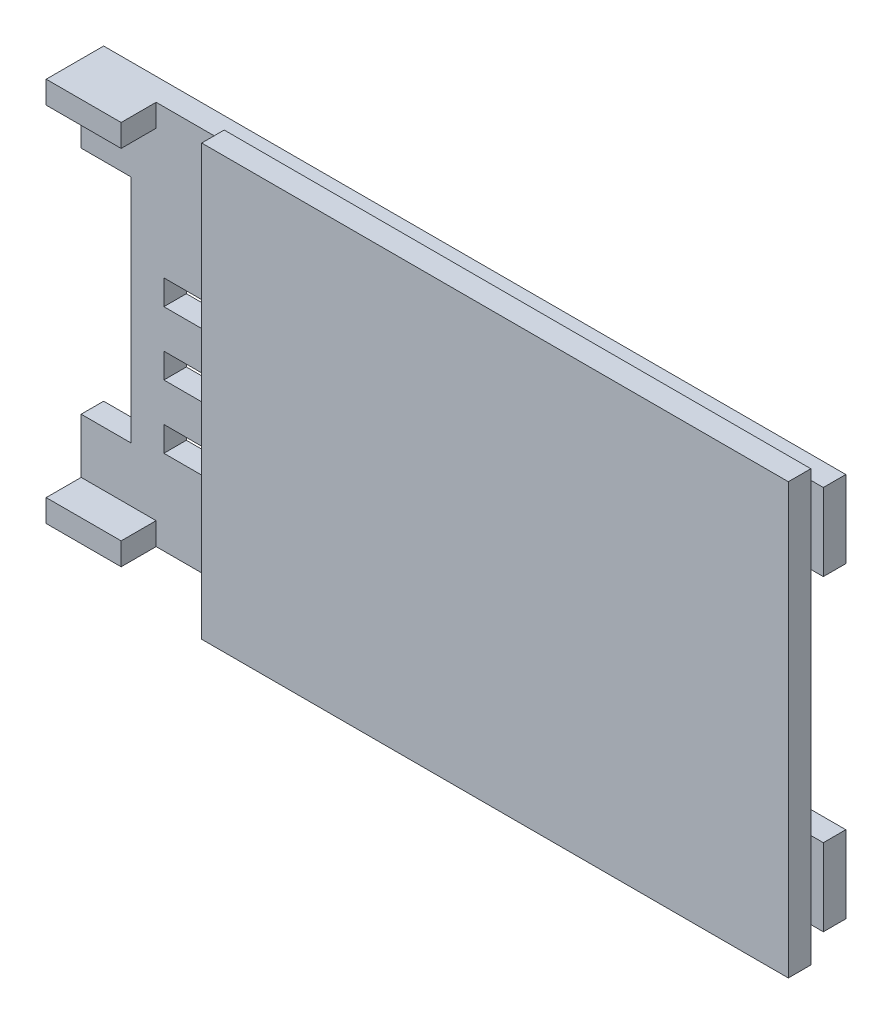
SolidWorks part; units mm, degrees
ref_plane "Front Plane" through (0, 0, 0) normal (0, 0, 1) x (1, 0, 0)
ref_plane "Top Plane" through (0, 0, 0) normal (0, 1, 0) x (1, 0, 0)
ref_plane "Right Plane" through (0, 0, 0) normal (1, 0, 0) x (0, 0, -1)
sketch "Sketch1" plane through (0, 0, 0) normal (0, 0, 1) x (1, 0, 0)
  line L0 (29.7, 12.31) -> (29.7, 15.4)
  line L1 (0, 0) -> (29.7, 0)
  line L2 (0, 0) -> (0, 3.09)
  line L3 (0, 15.4) -> (29.7, 15.4)
  line L4 (29.7, 0) -> (29.7, 3.09)
  line L5 (0, 12.31) -> (2, 12.31)
  line L6 (14.85, 15.4) -> (14.85, 0) construction
  line L7 (0, 3.09) -> (2, 3.09)
  line L8 (2, 12.31) -> (2, 3.09)
  line L9 (29.7, 12.31) -> (25.7, 12.31)
  line L10 (0, 12.31) -> (0, 15.4)
  line L11 (29.7, 3.09) -> (25.7, 3.09)
  line L12 (25.7, 12.31) -> (25.7, 3.09)
  line L13 (-2.6552, 7.7) -> (34.3923, 7.7) construction
  line L14 (-1.5692, 3.89) -> (31.5309, 3.89) construction
  line L15 (3.3098, 4.39) -> (9.6859, 4.39)
  line L16 (3.3098, 4.39) -> (3.3098, 3.39)
  line L17 (3.3098, 3.39) -> (9.6859, 3.39)
  line L18 (9.6859, 4.39) -> (9.6859, 3.39)
  line L19 (16.6164, 4.39) -> (22.3271, 4.39)
  line L20 (16.6164, 4.39) -> (16.6164, 3.39)
  line L21 (16.6164, 3.39) -> (22.3271, 3.39)
  line L22 (22.3271, 4.39) -> (22.3271, 3.39)
  line L23 (3.3098, 6.93) -> (9.6859, 6.93)
  line L24 (3.3098, 6.93) -> (3.3098, 5.93)
  line L25 (3.3098, 5.93) -> (9.6859, 5.93)
  line L26 (9.6859, 6.93) -> (9.6859, 5.93)
  line L27 (16.6164, 6.93) -> (22.3271, 6.93)
  line L28 (16.6164, 6.93) -> (16.6164, 5.93)
  line L29 (16.6164, 5.93) -> (22.3271, 5.93)
  line L30 (22.3271, 6.93) -> (22.3271, 5.93)
  line L31 (3.3098, 9.47) -> (9.6859, 9.47)
  line L32 (3.3098, 9.47) -> (3.3098, 8.47)
  line L33 (3.3098, 8.47) -> (9.6859, 8.47)
  line L34 (9.6859, 9.47) -> (9.6859, 8.47)
  line L35 (16.6164, 9.47) -> (22.3271, 9.47)
  line L36 (16.6164, 9.47) -> (16.6164, 8.47)
  line L37 (16.6164, 8.47) -> (22.3271, 8.47)
  line L38 (22.3271, 9.47) -> (22.3271, 8.47)
  point P17 (14.85, 7.7)
  point P18 (2, 7.7)
  point P19 (25.7, 7.7)
  point P30 (9.6859, 3.89)
  point P31 (22.3271, 3.89)
  dimension "D1" = 29.7
  dimension "D2" = 15.4
  dimension "D3" = 9.22
  dimension "D4" = 9.22
  dimension "D5" = 2
  dimension "D6" = 4
  dimension "D7" = 1
  dimension "D8" = 1
  dimension "D9" = 0.8
  dimension "D10" = 3
extrude "Boss-Extrude1" add sketch "Sketch1" along normal blind 0.9
ref_plane "Plane1" through (0, 0, 2.3) normal (0, 0, -1) x (-1, 0, 0)
sketch "Sketch4" plane through (0, 0, 0.9) normal (0, 0, 1) x (1, 0, 0)
  line L0 (25.7, 12.31) -> (25.7, 3.09) construction
  line L1 (0, 15.4) -> (3, 15.4)
  line L2 (0, 15.4) -> (0, 14.5)
  line L3 (0, 14.5) -> (3, 14.5)
  line L4 (3, 15.4) -> (3, 14.5)
  line L5 (25.7, 7.7) -> (2, 7.7) construction
  line L6 (2, 12.31) -> (2, 3.09) construction
  line L7 (3, 0) -> (3, 0.9)
  line L8 (0, 0.9) -> (3, 0.9)
  line L9 (0, 0) -> (0, 0.9)
  line L10 (0, 0) -> (3, 0)
  dimension "D1" = 3
  dimension "D2" = 0.9
extrude "Boss-Extrude3" add sketch "Sketch4" along normal up to surface (1.4 mm away) up to plane "Plane1"
sketch "Sketch5" plane through (0, 0, 2.3) normal (0, 0, -1) x (-1, 0, 0)
  line L0 (-25.7, 12.31) -> (-25.7, 3.09) construction
  line L1 (-6.2237, -0.9) -> (-29.7, -0.9)
  line L2 (-6.2237, -0.9) -> (-6.2237, 16.3)
  line L3 (-6.2237, 16.3) -> (-29.7, 16.3)
  line L4 (-29.7, -0.9) -> (-29.7, 16.3)
  line L5 (3.826, 7.7) -> (-37.3942, 7.7) construction
  point P10 (-25.7, 7.7)
  point P11 (-29.7, 7.7)
  dimension "D1" = 17.2
extrude "Boss-Extrude4" add sketch "Sketch5" along normal blind 0.9 separate body
